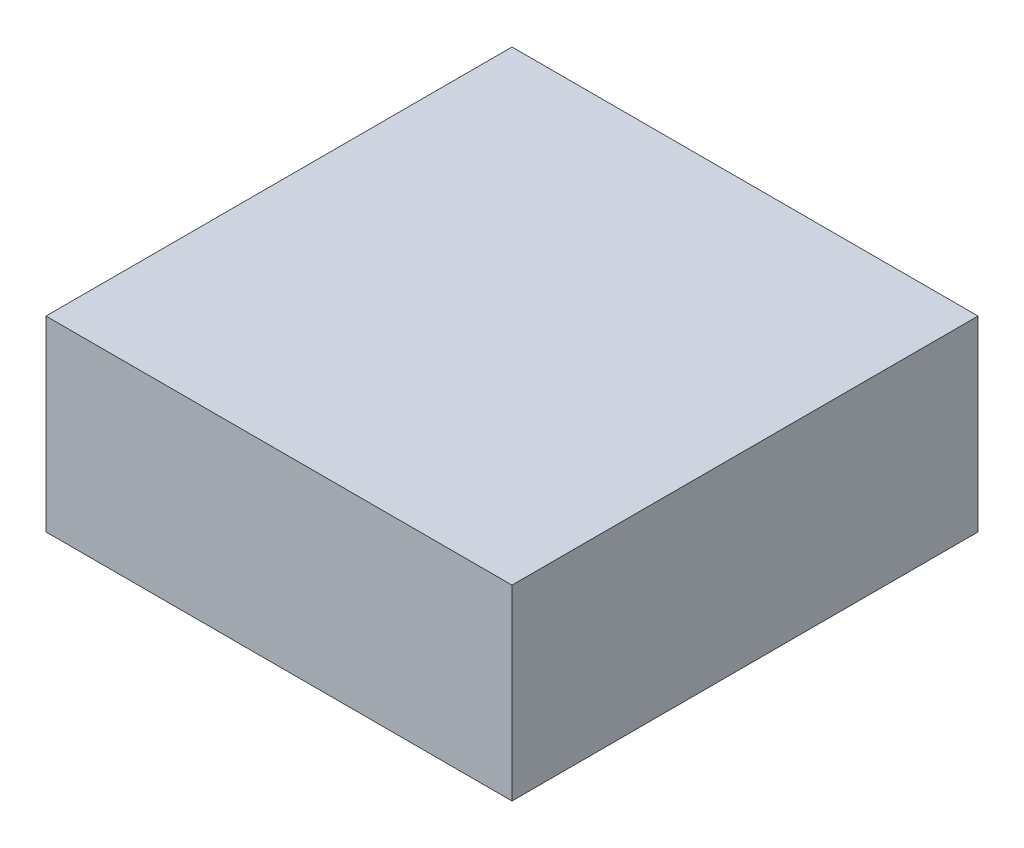
SolidWorks part; units mm, degrees
ref_plane "Front Plane" through (0, 0, 0) normal (0, 0, 1) x (1, 0, 0)
ref_plane "Top Plane" through (0, 0, 0) normal (0, 1, 0) x (1, 0, 0)
ref_plane "Right Plane" through (0, 0, 0) normal (1, 0, 0) x (0, 0, -1)
sketch "Sketch1" plane through (0, 0, 0) normal (0, 1, 0) x (1, 0, 0)
  line L1 (-3.925, 3.925) -> (3.925, 3.925)
  line L2 (-3.925, 3.925) -> (-3.925, -3.925)
  line L3 (-3.925, -3.925) -> (3.925, -3.925)
  line L4 (3.925, 3.925) -> (3.925, -3.925)
  line L5 (-3.925, 3.925) -> (3.925, -3.925) construction
  line L6 (-3.925, -3.925) -> (3.925, 3.925) construction
  point P0 (0, 0)
  dimension "D1" = 7.85
  dimension "D2" = 7.85
extrude "Boss-Extrude1" add sketch "Sketch1" against normal blind 3.15
shell "Shell1" thickness 1.5
